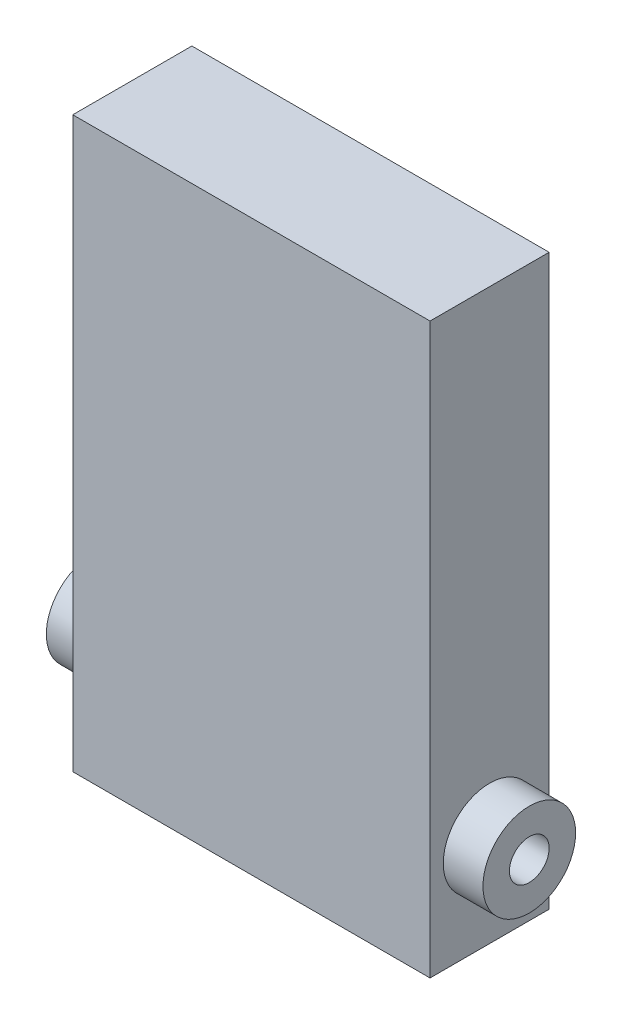
SolidWorks part; units mm, degrees
ref_plane "Alzado" through (0, 0, 0) normal (0, 0, 1) x (1, 0, 0)
ref_plane "Planta" through (0, 0, 0) normal (0, 1, 0) x (1, 0, 0)
ref_plane "Vista lateral" through (0, 0, 0) normal (1, 0, 0) x (0, 0, -1)
sketch "Croquis1" plane through (0, 0, 0) normal (0, 0, 1) x (1, 0, 0)
  line L1 (-13.5, 21.5) -> (13.5, 21.5)
  line L2 (-13.5, 21.5) -> (-13.5, -21.5)
  line L3 (-13.5, -21.5) -> (13.5, -21.5)
  line L4 (13.5, 21.5) -> (13.5, -21.5)
  line L5 (-13.5, 21.5) -> (13.5, -21.5) construction
  line L6 (-13.5, -21.5) -> (13.5, 21.5) construction
  point P0 (0, 0)
  dimension "D1" = 43
  dimension "D2" = 27
extrude "Saliente-Extruir1" add sketch "Croquis1" along normal mid plane 9
sketch "Croquis2" plane through (13.5, 0, 0) normal (1, 0, 0) x (0, 0, -1)
  line L0 (-4.5, -21.5) -> (4.5, -21.5) construction
  circle A0 centre (0, -14.5) radius 3.5
  point P2 (0, -16.1739)
  point P5 (0, 0)
  dimension "D1" = 7
  dimension "D2" = 7
extrude "Saliente-Extruir2" add sketch "Croquis2" along normal blind 3
sketch "Croquis3" plane through (16.5, 0, 0) normal (1, 0, 0) x (0, 0, -1)
  circle A0 centre (0, -14.5) radius 1.5
  dimension "D1" = 3
extrude "Cortar-Extruir1" cut sketch "Croquis3" against normal blind 5
mirror "Simetría2" about plane through (0, 0, 0) normal (1, 0, 0) of "Saliente-Extruir2", "Cortar-Extruir1"
